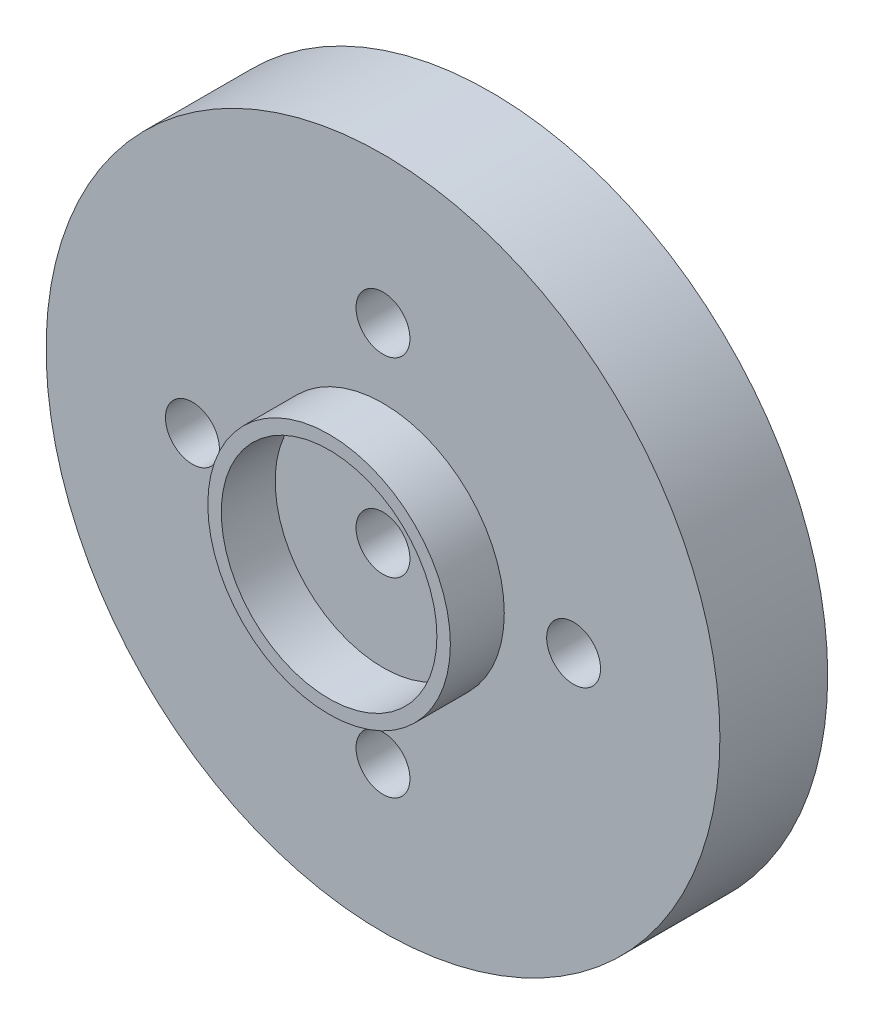
SolidWorks part; units mm, degrees
ref_plane "前视基准面" through (0, 0, 0) normal (0, 0, 1) x (1, 0, 0)
ref_plane "上视基准面" through (0, 0, 0) normal (0, 1, 0) x (1, 0, 0)
ref_plane "右视基准面" through (0, 0, 0) normal (1, 0, 0) x (0, 0, -1)
sketch "草图1" plane through (0, 0, 0) normal (0, 0, 1) x (1, 0, 0)
  line L0 (0, 0) -> (50000, 0) construction
  line L1 (0, 0) -> (0, 50000) construction
  circle A0 centre (0, 0) radius 12.5
extrude "凸台-拉伸1" add sketch "草图1" along normal blind 4 contours A0
sketch "草图2" plane through (0, 0, 4) normal (0, 0, 1) x (1, 0, 0)
  line L0 (0, 0) -> (50000, 0) construction
  line L1 (0, 0) -> (0, 50000) construction
  circle A0 centre (0, 0) radius 4.5
extrude "凸台-拉伸2" add sketch "草图2" along normal blind 2
sketch "草图3" plane through (0, 0, 4) normal (0, 0, 1) x (1, 0, 0)
  line L0 (0, 0) -> (50000, 0) construction
  line L1 (0, 0) -> (0, 50000) construction
  line L2 (0.1319, 0.1331) -> (35198.249, 35511.3081) construction
  circle A0 centre (4.9559, 5) radius 1
  circle A1 centre (4.9559, -5) radius 1
  circle A2 centre (-4.9559, -5) radius 1
  circle A3 centre (-4.9559, 5) radius 1
  dimension "D1" = 10
extrude "切除-拉伸3" cut sketch "草图3" against normal through all
sketch "草图4" plane through (0, 0, 6) normal (0, 0, 1) x (1, 0, 0)
  circle A0 centre (0, 0) radius 1
  circle A1 centre (0, 0) radius 4.5
extrude "切除-拉伸4" cut sketch "草图4" against normal through all contours A0
sketch "草图5" plane through (0, 0, 6) normal (0, 0, 1) x (1, 0, 0)
  circle A0 centre (0, 0) radius 4
extrude "切除-拉伸5" cut sketch "草图5" against normal blind 2 contours A0
sketch "草图6" plane through (0, 0, 0) normal (0, 0, -1) x (-1, 0, 0)
  line L0 (0, 0) -> (50000, 0) construction
  line L1 (0, 0) -> (0, 50000) construction
  circle A0 centre (0, 0) radius 12.5
extrude "凸台-拉伸3" add sketch "草图6" against normal blind 4
sketch "草图7" plane through (0, 0, 0) normal (0, 0, -1) x (-1, 0, 0)
  line L0 (0, 12.5) -> (0, -49987.5) construction
  line L1 (12.5, 0) -> (50012.5, 0) construction
  line L2 (0, 0) -> (35355.3391, 35355.3391) construction
  line L3 (0, 7.0711) -> (0, 0)
  line L4 (0, 0) -> (7.0711, 0)
  circle A2 centre (0, 0) radius 1
  circle A3 centre (0, 7.0711) radius 1
  circle A4 centre (7.0711, 0) radius 1
  circle A5 centre (-7.0711, 0) radius 1
  circle A6 centre (0, -7.0711) radius 1
  dimension "D1" = 10
extrude "切除-拉伸6" cut sketch "草图7" against normal blind 4
